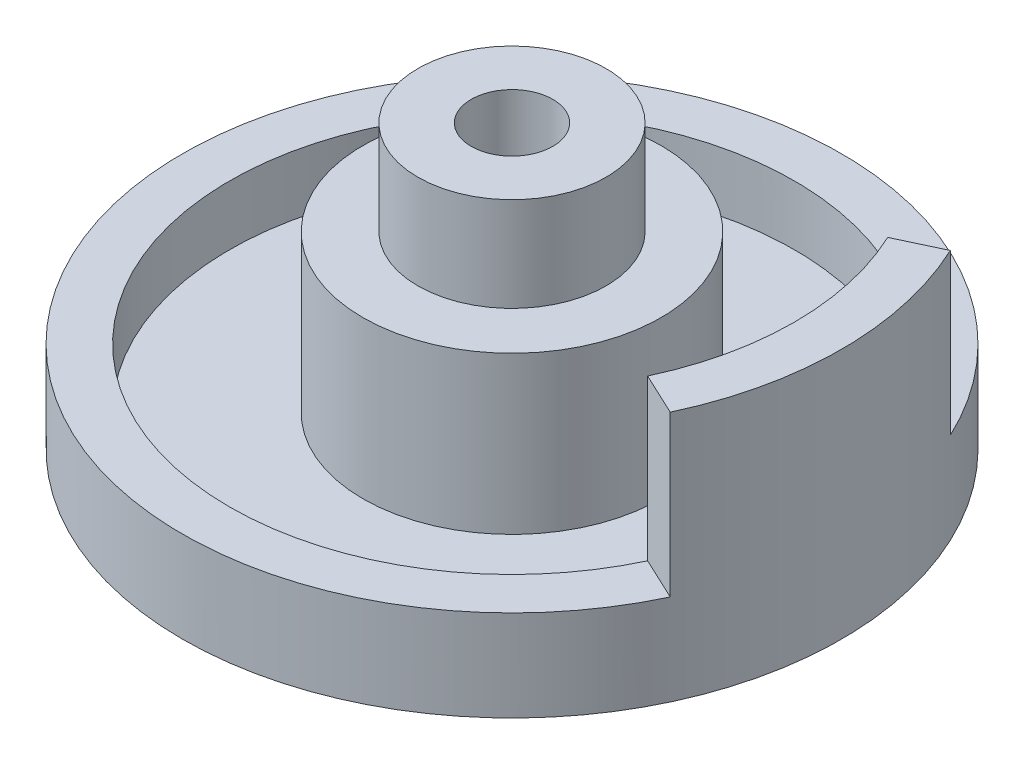
SolidWorks part; units mm, degrees
material "ABS PC"
ref_plane "Piano frontale" through (0, 0, 0) normal (0, 0, 1) x (1, 0, 0)
ref_plane "Piano superiore" through (0, 0, 0) normal (0, 1, 0) x (1, 0, 0)
ref_plane "Piano destro" through (0, 0, 0) normal (1, 0, 0) x (0, 0, -1)
sketch "Schizzo2" plane through (0, 0, 0) normal (0, 1, 0) x (1, 0, 0)
  circle A0 centre (0, 0) radius 10.5
  dimension "D1" = 21
extrude "Estrusione-Estrusione1" add sketch "Schizzo2" along normal blind 8
sketch "Schizzo3" plane through (0, 8, 0) normal (0, 1, 0) x (1, 0, 0)
  line L0 (0, 0) -> (8.1467, 3.825) construction
  line L1 (0, 0) -> (8.1467, -3.825) construction
  line L2 (8.1467, -3.825) -> (8.1467, 3.825) construction
  line L3 (8.1467, 3.825) -> (9.5045, 4.4625)
  line L4 (8.1467, -3.825) -> (9.5045, -4.4625)
  arc A0 (8.1467, -3.825) -> (8.1467, 3.825) centre (0, 0) ccw
  circle A1 centre (0, 0) radius 10.5 construction
  arc A2 (9.5045, 4.4625) -> (9.5045, -4.4625) centre (0, 0) ccw
  dimension "D1" = 18
  dimension "D2" = 7.65
extrude "Taglio-Estrusione1" cut sketch "Schizzo3" against normal blind 2
sketch "Schizzo4" plane through (0, 6, 0) normal (0, 1, 0) x (1, 0, 0)
  line L0 (8.1467, 3.825) -> (9.5045, 4.4625) construction
  line L1 (9.5045, -4.4625) -> (8.1467, -3.825) construction
  line L2 (8.1467, 3.825) -> (9.5045, 4.4625)
  line L3 (9.5045, -4.4625) -> (8.1467, -3.825)
  circle A0 centre (0, 0) radius 4.75
  arc A1 (8.1467, -3.825) -> (8.1467, 3.825) centre (0, 0) ccw construction
  arc A2 (9.5045, 4.4625) -> (9.5045, -4.4625) centre (0, 0) ccw construction
  arc A3 (8.1467, -3.825) -> (8.1467, 3.825) centre (0, 0) ccw
  arc A4 (9.5045, 4.4625) -> (9.5045, -4.4625) centre (0, 0) ccw
  dimension "D1" = 9.5
extrude "Taglio-Estrusione2" cut sketch "Schizzo4" against normal offset from surface (3.1 mm away) 2.9 up to face at (0, 0, 10.5)
sketch "Schizzo5" plane through (0, 2.9, 0) normal (0, 1, 0) x (1, 0, 0)
  circle A0 centre (0, 0) radius 9
  arc A1 (8.1467, -3.825) -> (8.1467, 3.825) centre (0, 0) ccw construction
  circle A2 centre (0, 0) radius 4.75 construction
  circle A3 centre (0, 0) radius 4.75
extrude "Taglio-Estrusione4" cut sketch "Schizzo5" against normal offset from surface (1.9 mm away) 1 up to face at (0, 0, 10.5)
sketch "Schizzo6" plane through (0, 6, 0) normal (0, 1, 0) x (1, 0, 0)
  circle A0 centre (0, 0) radius 3
  dimension "D1" = 6
extrude "Estrusione-Estrusione2" add sketch "Schizzo6" along normal blind 3
sketch "Schizzo7" plane through (0, 0, 0) normal (0, -1, 0) x (1, 0, 0)
  line L0 (1.5, -2.5981) -> (1.5, 2.5981)
  arc A0 (1.5, 2.5981) -> (1.5, -2.5981) centre (0, 0) ccw
  point P5 (1.5, 0)
  dimension "D1" = 6
  dimension "D2" = 1.5
extrude "Taglio-Estrusione5" cut sketch "Schizzo7" against normal blind 2.48
hole_wizard "Foro per Vite M2-1" positions "Schizzo9" profile "Schizzo11" hole size "M2" standard "Ansi Metric" end condition through all
sketch "Schizzo9" plane through (0, 9, 0) normal (0, 1, 0) x (1, 0, 0)
  point P0 (0, 0)
sketch "Schizzo11" plane through (0, 9, 0) normal (1, 0, 0) x (0, 0, 1)
  line L0 (0, 0) -> (0, 9)
  line L1 (0, 9) -> (1.3, 9)
  line L2 (1.3, 9) -> (1.3, 0)
  line L5 (1.3, 0) -> (0, 0)
  line L11 (0, -6.35) -> (0, 107.95) construction
  dimension "Thru Hole Dia." = 2.6
  dimension "Thru Hole Depth" = 9
